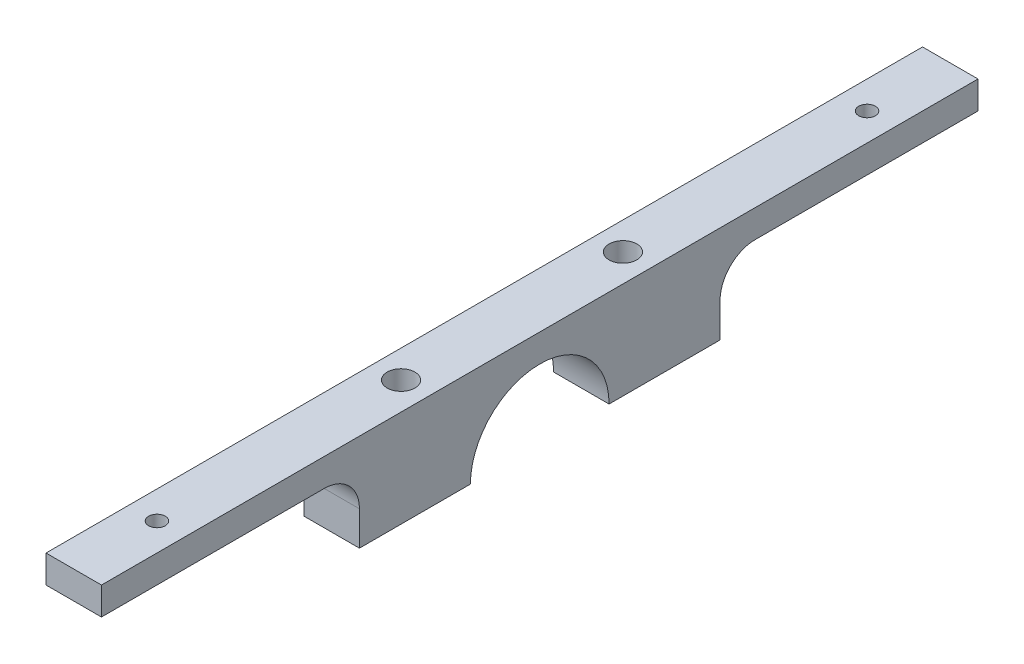
SolidWorks part; units mm, degrees
ref_plane "Front Plane" through (0, 0, 0) normal (0, 0, 1) x (1, 0, 0)
ref_plane "Top Plane" through (0, 0, 0) normal (0, 1, 0) x (1, 0, 0)
ref_plane "Right Plane" through (0, 0, 0) normal (1, 0, 0) x (0, 0, -1)
sketch "Sketch1" plane through (0, 0, 0) normal (1, 0, 0) x (0, 0, -1)
  line L6 (-79, 12.5) -> (-32.5, 12.5)
  line L7 (-32.5, 12.5) -> (-32.5, 0)
  line L8 (0, 0) -> (0, -50000) construction
  line L9 (-1000, 0) -> (-12.5, 0) construction
  line L10 (-79, 12.5) -> (-79, 17.5)
  line L11 (79, 12.5) -> (79, 17.5)
  line L12 (32.5, 12.5) -> (32.5, 0)
  line L13 (79, 12.5) -> (32.5, 12.5)
  line L16 (-79, 17.5) -> (79, 17.5)
  line L17 (-32.5, 0) -> (-12.5, 0)
  line L18 (12.5, 0) -> (32.5, 0)
  line L19 (12.5, 0) -> (50000, 0) construction
  arc A0 (12.5, 0) -> (-12.5, 0) centre (0, 0) ccw
  dimension "D1" = 25
  dimension "D5" = 20
  dimension "D4" = 17.5
  dimension "D3" = 158
  dimension "D6" = 5
extrude "Boss-Extrude1" add sketch "Sketch1" along normal blind 10
sketch "Sketch2" plane through (0, 12.5, 0) normal (0, -1, 0) x (1, 0, 0)
  line L0 (5, 79) -> (5, 32.5) construction
  line L1 (10, 79) -> (0, 79) construction
  line L2 (10, 32.5) -> (0, 32.5) construction
  line L6 (0, 0) -> (50000, 0) construction
  circle A2 centre (5, 64) radius 1.5
  circle A3 centre (5, -64) radius 1.5
  circle A6 centre (5, 20) radius 2.5
  circle A7 centre (5, -20) radius 2.5
  dimension "D1" = 3
  dimension "D2" = 64
  dimension "D5" = 5
  dimension "D6" = 20
extrude "Cut-Extrude1" cut sketch "Sketch2" against normal through all both and the other way through all
fillet "Fillet1" radius 6.35 2 edges at (5, 12.5, -32.5) (5, 12.5, 32.5)
